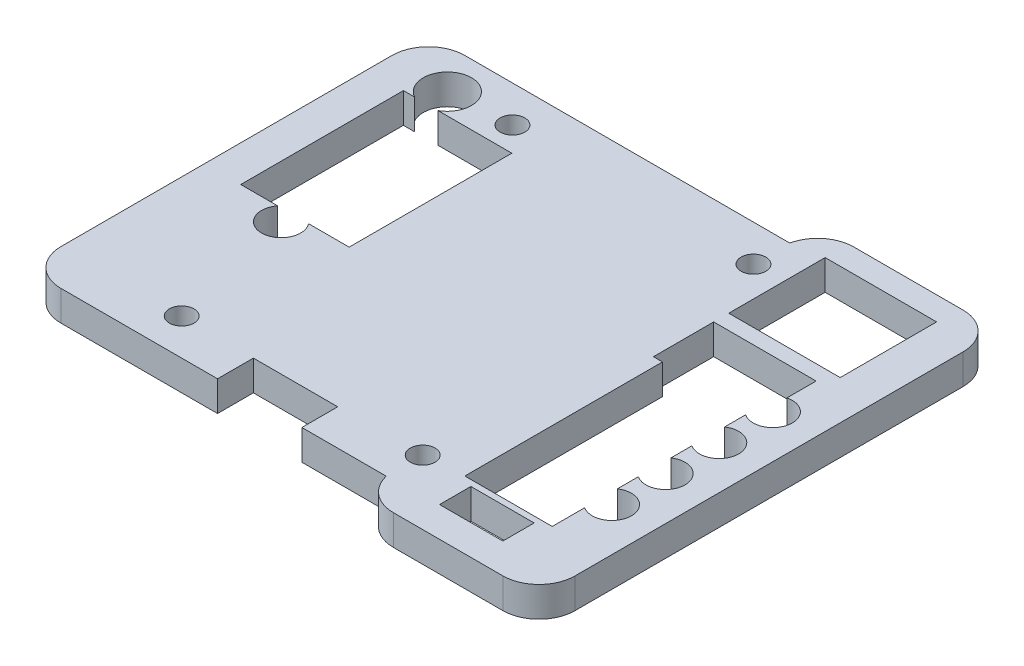
SolidWorks part; units mm, degrees
ref_plane "前视基准面" through (0, 0, 0) normal (0, 0, 1) x (1, 0, 0)
ref_plane "上视基准面" through (0, 0, 0) normal (0, 1, 0) x (1, 0, 0)
ref_plane "右视基准面" through (0, 0, 0) normal (1, 0, 0) x (0, 0, -1)
sketch "草图1" plane through (0, 0, 0) normal (0, 1, 0) x (1, 0, 0)
  line L0 (6, 0.3) -> (143.8, 0.3)
  line L1 (6, 0) -> (143.8, 0) construction
  line L2 (0, -6) -> (0, -68.8) construction
  line L3 (6, -74.8) -> (143.8, -74.8) construction
  line L4 (149.8, -6) -> (149.8, -68.8) construction
  line L5 (150.1, -6) -> (150.1, -68.8)
  line L6 (6, -75.1) -> (143.8, -75.1)
  line L7 (-0.3, -6) -> (-0.3, -68.8)
  arc A0 (143.8, 0) -> (149.8, -6) centre (143.8, -6) cw construction
  arc A1 (143.8, -74.8) -> (149.8, -68.8) centre (143.8, -68.8) ccw construction
  arc A2 (0, -68.8) -> (6, -74.8) centre (6, -68.8) ccw construction
  arc A3 (6, 0) -> (0, -6) centre (6, -6) ccw construction
  arc A4 (143.8, 0.3) -> (150.1, -6) centre (143.8, -6) cw
  arc A5 (143.8, -75.1) -> (150.1, -68.8) centre (143.8, -68.8) ccw
  arc A6 (-0.3, -68.8) -> (6, -75.1) centre (6, -68.8) ccw
  arc A7 (6, 0.3) -> (-0.3, -6) centre (6, -6) ccw
  point P7 (149.8, 0)
  point P12 (0, -74.8)
  point P15 (0, 0)
  dimension "D3" = 6
  dimension "D1" = 74.8
  dimension "D2" = 149.8
  dimension "D4" = 0.3
sketch "草图2" plane through (0, 0, 0) normal (0, -1, 0) x (-1, 0, 0)
  line L0 (-122.6, -55.35) -> (-108.9, -55.35) construction
  line L1 (-122.6, -69.85) -> (-108.9, -69.85) construction
  line L2 (-122.6, -69.85) -> (-122.6, -63.95) construction
  line L3 (-122.6, -63.95) -> (-108.9, -63.95) construction
  line L4 (-108.9, -69.85) -> (-108.9, -63.95) construction
  line L5 (-135.3, -1.25) -> (-35.3, -1.25) construction
  line L6 (-135.3, -1.25) -> (-135.3, -73.55) construction
  line L7 (-135.3, -73.55) -> (-35.3, -73.55) construction
  line L8 (-35.3, -1.25) -> (-35.3, -73.55) construction
  line L9 (-108.9, -61.25) -> (-108.9, -55.35) construction
  line L10 (-122.6, -61.25) -> (-108.9, -61.25) construction
  line L11 (-122.6, -61.25) -> (-122.6, -55.35) construction
  line L12 (-122.6, -46.75) -> (-108.9, -46.75) construction
  line L13 (-108.9, -52.65) -> (-108.9, -46.75) construction
  line L14 (-122.6, -52.65) -> (-108.9, -52.65) construction
  line L15 (-122.6, -52.65) -> (-122.6, -46.75) construction
  line L16 (-122.6, -38.15) -> (-108.9, -38.15) construction
  line L17 (-108.9, -44.05) -> (-108.9, -38.15) construction
  line L18 (-122.6, -44.05) -> (-108.9, -44.05) construction
  line L19 (-122.6, -44.05) -> (-122.6, -38.15) construction
  line L20 (0, -6) -> (0, -68.8) construction
  line L21 (-35.3, -73.55) -> (-0.8, -73.55) construction
  line L22 (-120.25, -26.65) -> (-111.25, -26.65) construction
  line L23 (-120.25, -26.65) -> (-120.25, -33.15) construction
  line L24 (-120.25, -33.15) -> (-111.25, -33.15) construction
  line L25 (-111.25, -26.65) -> (-111.25, -33.15) construction
  line L26 (-85.8, -48.75) -> (-81.1, -48.75) construction
  line L27 (-85.8, -48.75) -> (-85.8, -58.15) construction
  line L28 (-85.8, -58.15) -> (-81.1, -58.15) construction
  line L29 (-81.1, -48.75) -> (-81.1, -58.15) construction
  line L30 (-71.5, -48.65) -> (-68.2, -48.65) construction
  line L31 (-71.5, -48.65) -> (-71.5, -57.55) construction
  line L32 (-71.5, -57.55) -> (-68.2, -57.55) construction
  line L33 (-68.2, -48.65) -> (-68.2, -57.55) construction
  line L34 (-43.1, -45.05) -> (-38.6, -45.05) construction
  line L35 (-43.1, -45.05) -> (-43.1, -59.05) construction
  line L36 (-43.1, -59.05) -> (-38.6, -59.05) construction
  line L37 (-38.6, -45.05) -> (-38.6, -59.05) construction
  line L38 (-45.3, -61.55) -> (-40.8, -61.55) construction
  line L39 (-45.3, -61.55) -> (-45.3, -66.05) construction
  line L40 (-45.3, -66.05) -> (-40.8, -66.05) construction
  line L41 (-40.8, -61.55) -> (-40.8, -66.05) construction
  line L42 (-0.8, -73.55) -> (-0.8, -1.25) construction
  line L43 (-0.8, -1.25) -> (-35.3, -1.25) construction
  line L44 (-149.8, -6) -> (-149.8, -68.8) construction
  line L45 (-30.8, -34.65) -> (-27.3, -34.65) construction
  line L46 (-30.8, -34.65) -> (-30.8, -40.15) construction
  line L47 (-30.8, -40.15) -> (-27.3, -40.15) construction
  line L48 (-27.3, -34.65) -> (-27.3, -40.15) construction
  line L49 (-120.75, -33.65) -> (-110.75, -33.65)
  line L50 (-110.75, -26.15) -> (-110.75, -33.65)
  line L51 (-120.75, -26.15) -> (-110.75, -26.15)
  line L52 (-120.75, -26.15) -> (-120.75, -33.65)
  line L53 (-86.3, -48.25) -> (-86.3, -58.65)
  line L54 (-86.3, -58.65) -> (-80.6, -58.65)
  line L55 (-80.6, -48.25) -> (-80.6, -58.65)
  line L56 (-86.3, -48.25) -> (-80.6, -48.25)
  line L57 (-72, -48.15) -> (-72, -58.05)
  line L58 (-72, -58.05) -> (-67.7, -58.05)
  line L59 (-67.7, -48.15) -> (-67.7, -58.05)
  line L60 (-72, -48.15) -> (-67.7, -48.15)
  line L61 (-31.3, -34.15) -> (-31.3, -40.65)
  line L62 (-31.3, -40.65) -> (-26.8, -40.65)
  line L63 (-26.8, -34.15) -> (-26.8, -40.65)
  line L64 (-31.3, -34.15) -> (-26.8, -34.15)
  line L65 (-43.6, -44.55) -> (-43.6, -59.55)
  line L66 (-43.6, -59.55) -> (-38.1, -59.55)
  line L67 (-38.1, -44.55) -> (-38.1, -59.55)
  line L68 (-43.6, -44.55) -> (-38.1, -44.55)
  line L69 (-45.8, -61.05) -> (-45.8, -66.55)
  line L70 (-45.8, -66.55) -> (-40.3, -66.55)
  line L71 (-40.3, -61.05) -> (-40.3, -66.55)
  line L72 (-45.8, -61.05) -> (-40.3, -61.05)
  line L73 (-122.9, -44.35) -> (-108.6, -44.35)
  line L74 (-108.6, -44.35) -> (-108.6, -37.85)
  line L75 (-122.9, -37.85) -> (-108.6, -37.85)
  line L76 (-122.9, -44.35) -> (-122.9, -37.85)
  line L77 (-122.9, -52.95) -> (-108.6, -52.95)
  line L78 (-108.6, -52.95) -> (-108.6, -46.45)
  line L79 (-122.9, -46.45) -> (-108.6, -46.45)
  line L80 (-122.9, -52.95) -> (-122.9, -46.45)
  line L81 (-122.9, -61.55) -> (-108.6, -61.55)
  line L82 (-108.6, -61.55) -> (-108.6, -55.05)
  line L83 (-122.9, -55.05) -> (-108.6, -55.05)
  line L84 (-122.9, -61.55) -> (-122.9, -55.05)
  line L85 (-122.9, -70.15) -> (-108.6, -70.15)
  line L86 (-108.6, -70.15) -> (-108.6, -63.65)
  line L87 (-122.9, -63.65) -> (-108.6, -63.65)
  line L88 (-122.9, -70.15) -> (-122.9, -63.65)
  circle A0 centre (-103.2, -9.35) radius 1.65 construction
  circle A1 centre (-103.2, -64.25) radius 1.65 construction
  circle A2 centre (-63.2, -64.25) radius 1.65 construction
  circle A3 centre (-63.2, -9.35) radius 1.65 construction
  circle A4 centre (-130.8, -5.6) radius 1.25 construction
  circle A5 centre (-131.1, -55.65) radius 1.25 construction
  circle A6 centre (-47.7, -4.85) radius 1.25 construction
  circle A7 centre (-48.1, -68.75) radius 1.25 construction
  circle A8 centre (-22.8, -70.3) radius 1.25 construction
  circle A9 centre (-5.05, -71.05) radius 1.25 construction
  circle A10 centre (-5.05, -3.25) radius 1.25 construction
  circle A11 centre (-19, -37.4) radius 3.6 construction
  circle A12 centre (-103.2, -9.35) radius 2.05
  circle A13 centre (-63.2, -9.35) radius 2.05
  circle A14 centre (-63.2, -64.25) radius 2.05
  circle A15 centre (-103.2, -64.25) radius 2.05
  circle A16 centre (-19, -37.4) radius 4.1
  circle A17 centre (-130.8, -5.6) radius 1.75
  circle A18 centre (-131.1, -55.65) radius 1.75
  circle A19 centre (-48.1, -68.75) radius 1.75
  circle A20 centre (-22.8, -70.3) radius 1.75
  circle A21 centre (-5.05, -71.05) radius 1.75
  circle A22 centre (-5.05, -3.25) radius 1.75
  circle A23 centre (-47.7, -4.85) radius 1.75
  point P22 (0, -37.4)
  point P23 (-135.3, -37.4)
  point P28 (-115.75, -33.15)
  point P29 (-115.75, -38.15)
  point P30 (-111.25, -29.9)
  point P31 (-108.9, -41.1)
  point P79 (-0.8, -37.4)
  point P81 (-27.3, -37.4)
  dimension "D21" = 3.3
  dimension "D34" = 2.5
  dimension "D53" = 7.2
  dimension "D1" = 13.7
  dimension "D2" = 5.9
  dimension "D3" = 72.3
  dimension "D4" = 3.7
  dimension "D5" = 12.7
  dimension "D7" = 14.5
  dimension "D8" = 100
  dimension "D9" = 2.7
  dimension "D10" = 9
  dimension "D11" = 6.5
  dimension "D12" = 11.2
  dimension "D13" = 15.4
  dimension "D14" = 9.4
  dimension "D15" = 4.7
  dimension "D16" = 23.1
  dimension "D17" = 3.3
  dimension "D18" = 8.9
  dimension "D19" = 16
  dimension "D20" = 37.4
  dimension "D22" = 8.1
  dimension "D23" = 32.1
  dimension "D24" = 40
  dimension "D25" = 9.3
  dimension "D26" = 14
  dimension "D27" = 4.5
  dimension "D28" = 4.5
  dimension "D29" = 4.5
  dimension "D30" = 3.3
  dimension "D31" = 5.5
  dimension "D32" = 7.5
  dimension "D33" = 14.5
  dimension "D35" = 34.5
  dimension "D36" = 2
  dimension "D37" = 4.25
  dimension "D38" = 2.5
  dimension "D39" = 3.25
  dimension "D40" = 22
  dimension "D41" = 4.8
  dimension "D42" = 12.8
  dimension "D43" = 3.6
  dimension "D44" = 12.4
  dimension "D45" = 4.35
  dimension "D46" = 4.5
  dimension "D47" = 4.2
  dimension "D48" = 17.9
  dimension "D49" = 18.2
  dimension "D50" = 3.5
  dimension "D51" = 5.5
  dimension "D52" = 8.3
  dimension "D54" = 0.4
  dimension "D55" = 0.5
  dimension "D56" = 0.5
  dimension "D57" = 0.5
  dimension "D58" = 0.3
  dimension "D6" = 4
sketch "草图3" plane through (0, 0, 0) normal (0, 1, 0) x (1, 0, 0)
  line L0 (135.3, -1.25) -> (135.3, -73.55) construction
  line L1 (143.8, 0) -> (135.3, 0)
  line L2 (149.8, -6) -> (149.8, -68.8)
  line L3 (143.8, -74.8) -> (135.3, -74.8)
  line L4 (135.3, 0) -> (135.3, -74.8)
  line L5 (6, -74.8) -> (143.8, -74.8) construction
  arc A0 (143.8, 0) -> (149.8, -6) centre (143.8, -6) cw
  arc A1 (149.8, -68.8) -> (143.8, -74.8) centre (143.8, -68.8) cw
  point P17 (149.8, 0)
  dimension "D1" = 6
sketch "草图4" plane through (0, 0, 0) normal (0, 1, 0) x (1, 0, 0)
  line L0 (122.9, -62.85) -> (108.6, -62.85)
  line L1 (122.6, -63.15) -> (108.9, -63.15) construction
  line L2 (122.6, -63.15) -> (122.6, -70.65) construction
  line L3 (122.6, -70.65) -> (108.9, -70.65) construction
  line L4 (108.9, -63.15) -> (108.9, -70.65) construction
  line L5 (122.6, -69.85) -> (122.6, -63.95) construction
  line L6 (108.6, -62.85) -> (108.6, -70.95)
  line L7 (108.9, -69.85) -> (108.9, -63.95) construction
  line L8 (122.6, -54.55) -> (108.9, -54.55) construction
  line L9 (108.9, -54.55) -> (108.9, -62.05) construction
  line L10 (122.6, -62.05) -> (108.9, -62.05) construction
  line L11 (122.6, -54.55) -> (122.6, -62.05) construction
  line L12 (122.6, -45.95) -> (108.9, -45.95) construction
  line L13 (108.9, -45.95) -> (108.9, -53.45) construction
  line L14 (122.6, -53.45) -> (108.9, -53.45) construction
  line L15 (122.6, -45.95) -> (122.6, -53.45) construction
  line L16 (122.6, -37.35) -> (108.9, -37.35) construction
  line L17 (108.9, -37.35) -> (108.9, -44.85) construction
  line L18 (122.6, -44.85) -> (108.9, -44.85) construction
  line L19 (122.6, -37.35) -> (122.6, -44.85) construction
  line L20 (122.9, -70.95) -> (108.6, -70.95)
  line L21 (122.9, -62.85) -> (122.9, -70.95)
  line L22 (122.9, -54.25) -> (108.6, -54.25)
  line L23 (108.6, -54.25) -> (108.6, -62.35)
  line L24 (122.9, -62.35) -> (108.6, -62.35)
  line L25 (122.9, -54.25) -> (122.9, -62.35)
  line L26 (122.9, -45.65) -> (108.6, -45.65)
  line L27 (108.6, -45.65) -> (108.6, -53.75)
  line L28 (122.9, -53.75) -> (108.6, -53.75)
  line L29 (122.9, -45.65) -> (122.9, -53.75)
  line L30 (122.9, -37.05) -> (108.6, -37.05)
  line L31 (108.6, -37.05) -> (108.6, -45.15)
  line L32 (122.9, -45.15) -> (108.6, -45.15)
  line L33 (122.9, -37.05) -> (122.9, -45.15)
  point P11 (108.9, -66.9)
  point P12 (108.9, -66.9)
  dimension "D1" = 7.5
  dimension "D3" = 1.1
  dimension "D4" = 0.3
  dimension "D2" = 4
extrude "拉伸-薄壁1" add sketch "草图2" along normal blind 5 thin contours A13 | A12 | A14 | A15
sketch "草图6" plane through (0, 0, 0) normal (0, 1, 0) x (1, 0, 0)
  line L0 (127.2, 1.45) -> (109.0462, 1.45)
  line L1 (133.2, -4.55) -> (133.2, -68.95)
  line L2 (127.2, -74.95) -> (109.0462, -74.95)
  line L3 (33.4345, -36.75) -> (43.3021, -36.75) construction
  line L4 (63.2, -3.3) -> (103.1778, -3.3)
  line L6 (63.2, -3.3) -> (49.25, -3.3)
  line L10 (122.9, -70.95) -> (108.6, -70.95) construction
  line L11 (108.6, -62.85) -> (108.6, -70.95) construction
  line L12 (43.2, -9.35) -> (43.2, -64.3)
  line L13 (103.2, -70.3) -> (49.2, -70.3)
  circle A1 centre (103.2, -64.25) radius 6.05 construction
  arc A3 (133.2, -4.55) -> (127.2, 1.45) centre (127.2, -4.55) ccw
  arc A4 (109.0462, -74.95) -> (103.2, -70.3) centre (109.0462, -68.95) cw
  circle A5 centre (63.2, -64.25) radius 6.05 construction
  arc A6 (133.2, -68.95) -> (127.2, -74.95) centre (127.2, -68.95) cw
  arc A7 (109.0462, 1.45) -> (103.1778, -3.3) centre (109.0462, -4.55) ccw
  circle A8 centre (63.2, -9.35) radius 6.05 construction
  arc A9 (43.2, -64.3) -> (49.2, -70.3) centre (49.2, -64.3) ccw
  circle A10 centre (103.2, -9.35) radius 2.05 construction
  circle A11 centre (103.2, -64.25) radius 2.05 construction
  circle A12 centre (63.2, -64.25) radius 2.05 construction
  circle A13 centre (103.2, -9.35) radius 2.05
  circle A14 centre (103.2, -64.25) radius 2.05
  circle A15 centre (63.2, -64.25) radius 2.05
  circle A16 centre (63.2, -9.35) radius 2.05 construction
  circle A17 centre (63.2, -9.35) radius 2.05
  arc A18 (49.25, -3.3) -> (43.2, -9.35) centre (49.25, -9.35) ccw
  point P37 (105.6, -74.95)
  point P42 (130.9, -6.15)
  dimension "D6" = 6
  dimension "D7" = 12.1
  dimension "D8" = 6
  dimension "D9" = 6
  dimension "D10" = 6
  dimension "D11" = 6
  dimension "D2" = 27.5
  dimension "D3" = 4
  dimension "D4" = 3
  dimension "D5" = 20
  dimension "D12" = 30
extrude "凸台-拉伸1" add sketch "草图6" against normal up to surface (5 mm away) up to face at (97.15, -5, 9.35)
sketch "草图7" plane through (0, -5, 3) normal (0, -1, 0) x (1, 0, 0)
  line L9 (80.466, 15.85) -> (96.6871, 15.85) construction
  line L43 (107.2, -14.628) -> (107.2, -27.7853) construction
  line L44 (108.9, 22) -> (108.9, 67) construction
  line L45 (122.6, 67) -> (108.9, 67) construction
  line L46 (122.6, 22) -> (122.6, 67) construction
  line L47 (122.6, 22) -> (108.9, 22) construction
  line L48 (120.2, 9.55) -> (113.2, 9.55)
  line L49 (120.2, 4.55) -> (120.2, 9.55)
  line L50 (113.2, 4.55) -> (120.2, 4.55)
  line L51 (113.2, 9.55) -> (113.2, 4.55)
  line L52 (80.4, 48.65) -> (80.4, 33.65)
  line L53 (85.4, 48.65) -> (80.4, 48.65)
  line L54 (97.9, 36.55) -> (89.9, 36.55)
  line L55 (97.9, 25.55) -> (97.9, 36.55)
  line L56 (89.9, 25.55) -> (97.9, 25.55)
  line L57 (89.9, 36.55) -> (89.9, 25.55)
  line L58 (66.4, 33.65) -> (80.4, 33.65)
  line L59 (50.4, 54.65) -> (50.4, 33.65)
  line L60 (85.4, 54.65) -> (50.4, 54.65)
  line L61 (85.4, 48.65) -> (85.4, 54.65)
  line L62 (47.4, 10.15) -> (66.4, 10.15)
  line L63 (47.4, 33.65) -> (47.4, 10.15)
  line L64 (50.4, 33.65) -> (47.4, 33.65)
  line L65 (66.4, 10.15) -> (66.4, 15.35)
  line L66 (66.4, 24.35) -> (72.4, 24.35)
  line L67 (66.4, 24.35) -> (66.4, 33.65)
  line L68 (72.4, 15.35) -> (66.4, 15.35)
  line L69 (122.9, 21.7) -> (122.9, 67.3)
  line L70 (122.9, 67.3) -> (108.6, 67.3)
  line L71 (72.4, 24.35) -> (72.4, 15.35)
  line L72 (92.2, 15.35) -> (75.2, 15.35)
  line L73 (92.2, 23.55) -> (92.2, 15.35)
  line L74 (75.2, 23.55) -> (92.2, 23.55)
  line L75 (107.7, 23.55) -> (107.7, 15.35)
  line L76 (98.2, 23.55) -> (107.7, 23.55)
  line L77 (98.2, 15.35) -> (98.2, 23.55)
  line L78 (107.7, 15.35) -> (98.2, 15.35)
  line L79 (75.2, 15.35) -> (75.2, 23.55)
  line L80 (108.6, 21.7) -> (108.6, 67.3)
  line L81 (122.9, 21.7) -> (108.6, 21.7)
  circle A0 centre (103.2, 61.25) radius 2.05 construction
  circle A1 centre (103.2, 61.25) radius 2.05
  circle A5 centre (59.2, 61.25) radius 2.05
  circle A6 centre (103.2, 61.25) radius 2.05
extrude "切除-拉伸1" [suppressed] cut sketch "草图7" against normal blind 5 contours L81 L69 L70 L80 | L78 L75 L76 L77 | L54 L57 L56 L55 | L79 L72 L73 L74 | L71 L66 L67 L58 L52 L53 L61 L60 L59 L64 L63 L62 L65 L68
sketch "草图8" plane through (0, 0, 0) normal (0, -1, 0) x (1, 0, 0)
  line L9 (80.466, -18.85) -> (96.6871, -18.85) construction
  line L10 (107.2, 11.628) -> (107.2, 24.7853) construction
  line L14 (5.1637, 36.85) -> (19.0276, 36.85) construction
  line L18 (63.2, 64.25) -> (46.0308, 64.25) construction
  line L19 (67.2, 40.45) -> (49.2, 40.45)
  line L22 (67.2, 13.45) -> (67.2, 40.45)
  line L23 (49.2, 13.45) -> (67.2, 13.45)
  line L24 (49.2, 40.45) -> (49.2, 13.45)
  line L25 (98.5, 35.95) -> (89.5, 35.95)
  line L26 (98.5, 23.45) -> (98.5, 35.95)
  line L27 (89.5, 23.45) -> (98.5, 23.45)
  line L28 (89.5, 35.95) -> (89.5, 23.45)
  line L29 (108.2, 30.95) -> (125.2, 30.95) construction
  line L30 (126.7, 18.45) -> (108.2, 18.45)
  line L31 (126.7, 2.45) -> (126.7, 18.45)
  line L32 (108.2, 2.45) -> (126.7, 2.45)
  line L37 (108.2, 18.45) -> (108.2, 2.45)
  line L38 (125.2, 20.95) -> (125.2, 30.95)
  line L47 (125.2, 30.95) -> (124.2, 30.95)
  line L48 (108.2, 30.95) -> (108.2, 20.95)
  line L49 (108.2, 30.95) -> (109.7, 30.95)
  line L50 (125.2, 20.95) -> (108.2, 20.95)
  line L51 (111.7, 64.75) -> (122.2, 64.75)
  line L52 (122.2, 62.75) -> (122.2, 69.95)
  line L53 (124.2, 30.95) -> (124.2, 63.75)
  line L54 (109.7, 63.75) -> (124.2, 63.75)
  line L55 (111.7, 69.95) -> (122.2, 69.95)
  line L56 (111.7, 69.95) -> (111.7, 62.75)
  line L57 (109.7, 30.95) -> (109.7, 63.75)
  line L58 (75.2, 64.35) -> (89.2, 64.35)
  line L59 (75.2, 73.35) -> (75.2, 64.35)
  line L60 (89.2, 73.35) -> (75.2, 73.35)
  line L61 (89.2, 64.35) -> (89.2, 73.35)
  circle A0 centre (53, 9.95) radius 4
  circle A1 centre (57.9, 42.45) radius 3.25
  circle A2 centre (103.2, 9.35) radius 2.4
  circle A3 centre (126, 55.65) radius 3.25
  circle A4 centre (63.2, 9.35) radius 2.4
  circle A5 centre (103.2, 64.25) radius 2.4 construction
  circle A10 centre (126, 46.75) radius 3.25
  circle A11 centre (63.2, 64.25) radius 2.4 construction
  circle A14 centre (126, 37.85) radius 3.25
  circle A15 centre (126, 28.95) radius 3.25
  dimension "D7" = 27.5
  dimension "D1" = 10
extrude "切除-拉伸2" cut sketch "草图8" along normal through all
equation "\"D1@草图3\"=\"D3@草图1\""
